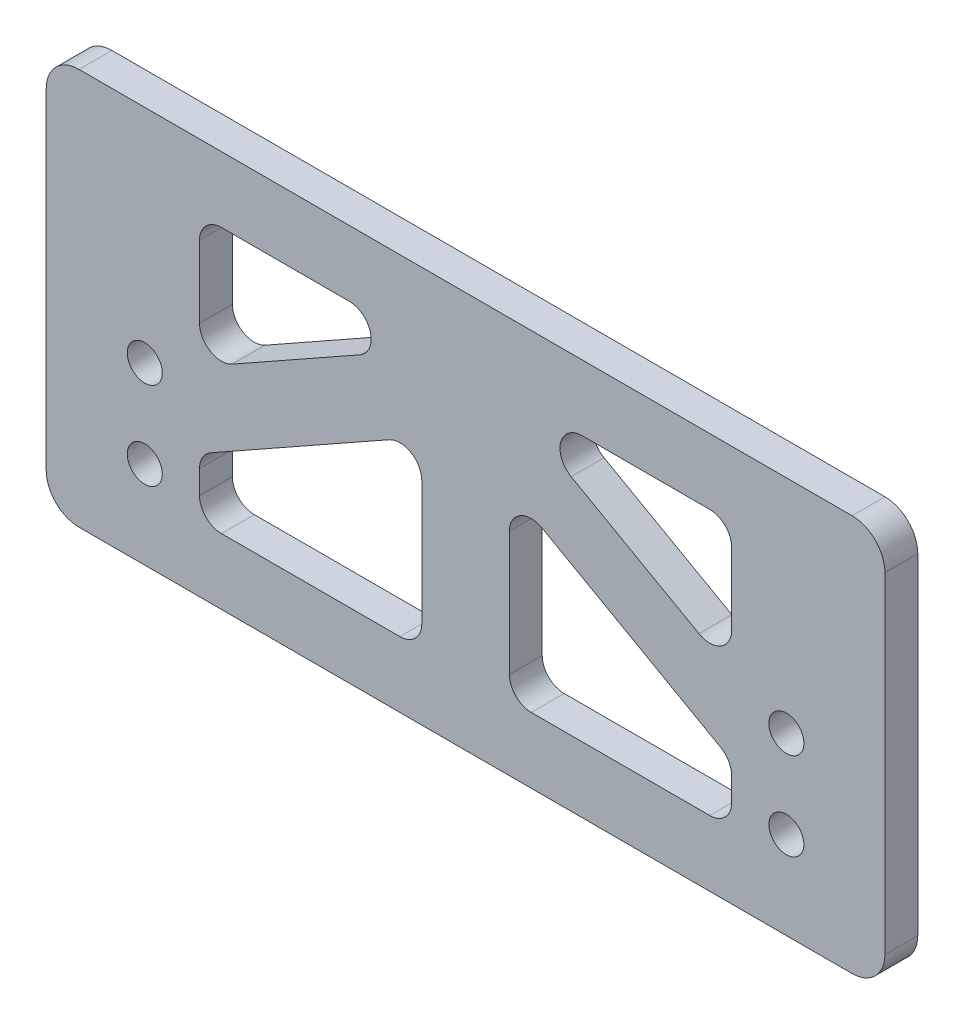
SolidWorks part; units mm, degrees
material "Thornel Mat VMA"
ref_plane "前视基准面" through (0, 0, 0) normal (0, 0, 1) x (1, 0, 0)
ref_plane "上视基准面" through (0, 0, 0) normal (0, 1, 0) x (1, 0, 0)
ref_plane "右视基准面" through (0, 0, 0) normal (1, 0, 0) x (0, 0, -1)
sketch "草图1" plane through (0, 0, 0) normal (0, 0, 1) x (1, 0, 0)
  line L0 (0, 66.325) -> (76.6, 66.325)
  line L1 (76.6, 66.325) -> (76.6, 30.1147)
  line L2 (76.6, 30.1147) -> (0, 30.1147)
  line L3 (0, 30.1147) -> (0, 66.325)
  line L4 (5, 33.1147) -> (5, 55.1147) construction
  line L5 (38.3, 66.325) -> (38.3, 55.1202) construction
  circle A0 centre (9, 38.1147) radius 1.6
  circle A1 centre (9, 46.1147) radius 1.6
  circle A2 centre (67.6, 38.1147) radius 1.6
  circle A3 centre (67.6, 46.1147) radius 1.6
  dimension "D1" = 3.2
  dimension "D4" = 4
  dimension "D5" = 3.2
  dimension "D2" = 4
  dimension "D3" = 8
  dimension "D6" = 8
extrude "凸台-拉伸1" add sketch "草图1" along normal blind 3
fillet "圆角1" radius 3 4 edges at (76.6, 66.325, 1.5) (76.6, 30.1147, 1.5) (0, 30.1147, 1.5) (0, 66.325, 1.5)
sketch "草图2" plane through (0, 0, 3) normal (0, 0, 1) x (1, 0, 0)
  line L0 (38.3, 66.325) -> (38.3, 30.1147) construction
  line L1 (73.6, 66.325) -> (3, 66.325) construction
  line L2 (3, 30.1147) -> (73.6, 30.1147) construction
  line L3 (14, 60.325) -> (35.3, 60.325)
  line L4 (14, 60.325) -> (14, 48.325)
  line L5 (14, 48.325) -> (35.3, 60.325)
  line L6 (0, 63.325) -> (0, 33.1147) construction
  line L7 (62.6, 48.325) -> (41.3, 60.325)
  line L8 (62.6, 60.325) -> (62.6, 48.325)
  line L9 (62.6, 60.325) -> (41.3, 60.325)
  line L10 (34.3, 52.8749) -> (14, 41.4383)
  line L11 (14, 41.4383) -> (14, 36.1147)
  line L12 (14, 36.1147) -> (34.3, 36.1147)
  line L13 (62.6, 41.4383) -> (62.6, 36.1147)
  line L14 (42.3, 52.8749) -> (62.6, 41.4383)
  line L15 (34.3, 36.1147) -> (34.3, 52.8749)
  line L16 (42.3, 36.1147) -> (42.3, 52.8749)
  line L17 (42.3, 36.1147) -> (62.6, 36.1147)
  point P19 (38.3, 36.1147)
  dimension "D1" = 6
  dimension "D2" = 14
  dimension "D3" = 12
  dimension "D4" = 3
  dimension "D5" = 6
  dimension "D6" = 6
  dimension "D7" = 4
  dimension "D8" = 4
extrude "切除-拉伸1" cut sketch "草图2" against normal through all
fillet "圆角2" radius 2 14 edges at (62.6, 60.325, 1.5) (62.6, 48.325, 1.5) (62.6, 36.1147, 1.5) (62.6, 41.4383, 1.5) (42.3, 52.8749, 1.5) (42.3, 36.1147, 1.5) (34.3, 36.1147, 1.5) (14, 36.1147, 1.5) (14, 41.4383, 1.5) (34.3, 52.8749, 1.5) (14, 48.325, 1.5) (14, 60.325, 1.5) (41.3, 60.325, 1.5) (35.3, 60.325, 1.5)
